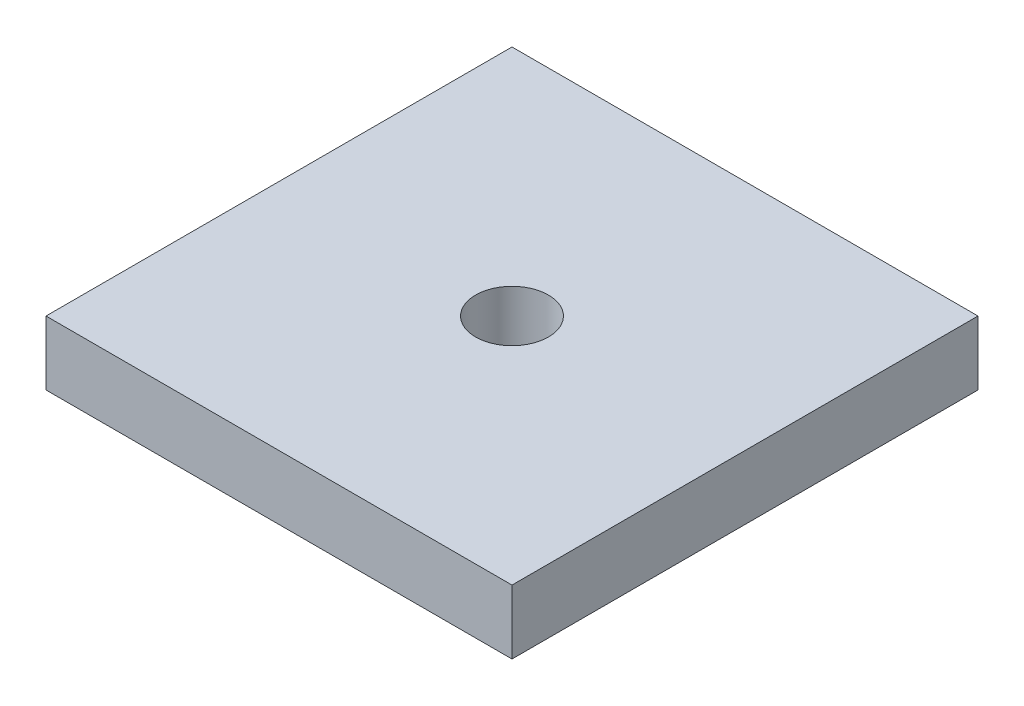
SolidWorks part; units mm, degrees
ref_plane "Front Plane" through (0, 0, 0) normal (0, 0, 1) x (1, 0, 0)
ref_plane "Top Plane" through (0, 0, 0) normal (0, 1, 0) x (1, 0, 0)
ref_plane "Right Plane" through (0, 0, 0) normal (1, 0, 0) x (0, 0, -1)
sketch "Sketch1" plane through (0, 0, 0) normal (0, 1, 0) x (1, 0, 0)
  line L1 (0, 0) -> (16, 0)
  line L2 (0, 0) -> (0, 16)
  line L3 (0, 16) -> (16, 16)
  line L4 (16, 0) -> (16, 16)
  circle A0 centre (8, 8) radius 1.25
  point P7 (16, 8)
  point P8 (8, 0)
  dimension "D3" = 2.5
  dimension "D1" = 16
  dimension "D2" = 16
extrude "Boss-Extrude1" add sketch "Sketch1" along normal blind 2.2
